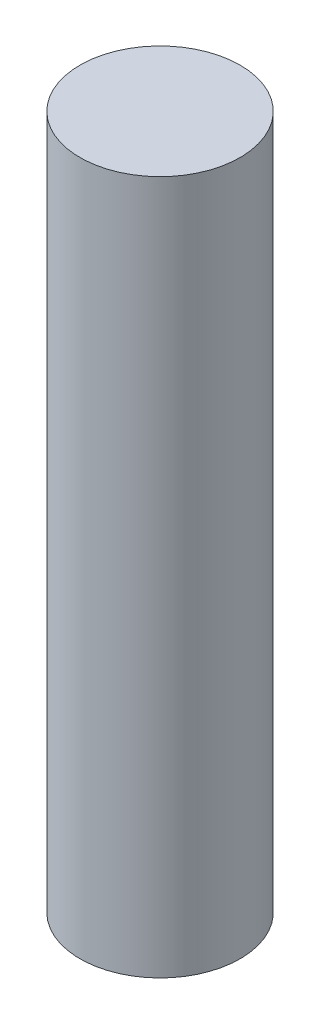
SolidWorks part; units mm, degrees
material "Tin Bearing Bronze"
ref_plane "Спереди" through (0, 0, 0) normal (0, 0, 1) x (1, 0, 0)
ref_plane "Сверху" through (0, 0, 0) normal (0, 1, 0) x (1, 0, 0)
ref_plane "Справа" through (0, 0, 0) normal (1, 0, 0) x (0, 0, -1)
other "Configuration Table"
sketch "Sketch1" plane through (0, 0, 0) normal (0, 0, 1) x (1, 0, 0)
  line L1 (0, 0) -> (1.5, 0)
  line L2 (0, 0) -> (0, 11)
  line L3 (0, 11) -> (1.5, 11)
  line L4 (1.5, 0) -> (1.5, 11)
  line L5 (0, 11) -> (3, 11)
  line L6 (0, 11) -> (0, 13)
  line L7 (0, 13) -> (3, 13)
  line L8 (3, 11) -> (3, 13)
  line L9 (0, 13) -> (1.5, 13)
  line L10 (0, 13) -> (0, 11)
  line L11 (0, 11) -> (1.5, 11)
  line L12 (1.5, 13) -> (1.5, 11)
  dimension "D1" = 2
  dimension "D2" = 3
  dimension "D3" = 1.5
  dimension "D4" = 11
revolve "Revolve1" add sketch "Sketch1" angle 360 about L6
equation "\"length\"= 11"
equation "\"D4@Sketch1\"=\"length\""
